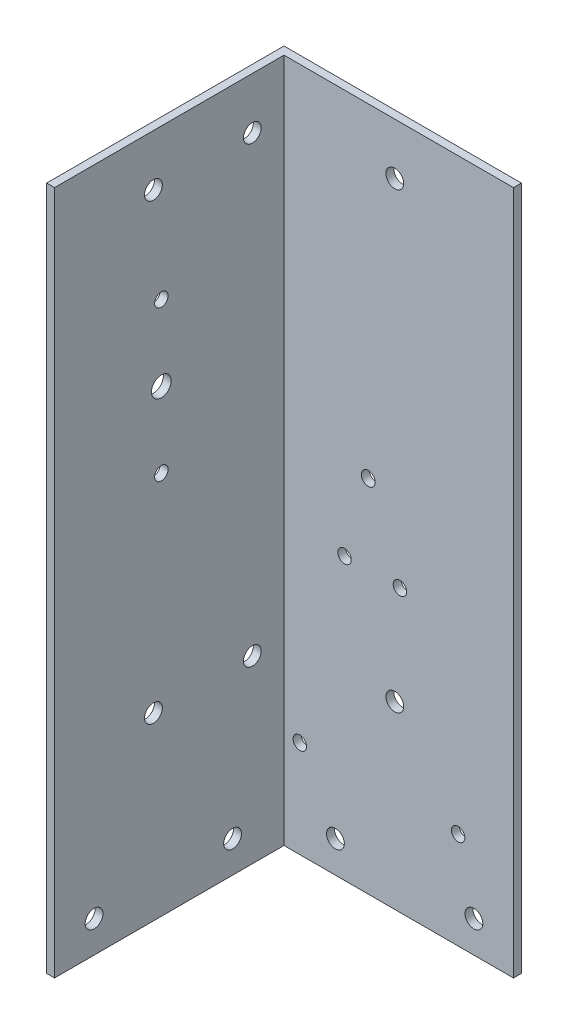
SolidWorks part; units mm, degrees
ref_plane "Ebene vorne" through (0, 0, 0) normal (0, 0, 1) x (1, 0, 0)
ref_plane "Ebene oben" through (0, 0, 0) normal (0, 1, 0) x (1, 0, 0)
ref_plane "Ebene rechts" through (0, 0, 0) normal (1, 0, 0) x (0, 0, -1)
sketch "Skizze1" plane through (0, 0, 0) normal (0, 1, 0) x (1, 0, 0)
  line L0 (0, 0) -> (0, -60)
  line L1 (0, 0) -> (60, 0)
  dimension "D1" = 60
  dimension "D2" = 60
extrude "Linear-Austragen-Dünn1" add sketch "Skizze1" along normal blind 173 thin thin type one direction wall 2
hole_wizard "Durchgangsloch für M41" positions "Skizze2" profile "Skizze3" hole size "M4" standard "DIN" end condition up to next
sketch "Skizze2" plane through (0, 0, 0) normal (-1, 0, 0) x (0, 0, 1)
  line L2 (10, 160) -> (35, 160) construction
  line L4 (60, 173) -> (0, 173) construction
  line L5 (0, 173) -> (0, 0) construction
  point P0 (35, 160)
  point P3 (10, 160)
  dimension "D1" = 13
  dimension "D2" = 25
  dimension "D3" = 10
sketch "Skizze3" plane through (0, 160, 35) normal (0, 1, 0) x (0, 0, 1)
  line L0 (0, 0) -> (0, 2)
  line L1 (0, 2) -> (2.25, 2)
  line L2 (2.25, 2) -> (2.25, 0)
  line L5 (2.25, 0) -> (0, 0)
  line L11 (0, -6.35) -> (0, 107.95) construction
  dimension "Bohrerdurchmesser" = 4.5
  dimension "Bohrungstiefe" = 2
hole_wizard "Durchgangsloch für M42" positions "Skizze4" profile "Skizze5" hole size "M4" standard "DIN" end condition up to next
sketch "Skizze4" plane through (0, 0, 0) normal (-1, 0, 0) x (0, 0, 1)
  line L0 (15, 8) -> (50, 8) construction
  line L2 (10, 45.5) -> (35, 45.5) construction
  line L4 (0, 173) -> (0, 0) construction
  circle A0 centre (35, 160) radius 2.25 construction
  point P0 (35, 45.5)
  point P8 (10, 45.5)
  point P12 (50, 8)
  point P15 (15, 8)
  dimension "D1" = 152
  dimension "D2" = 37.5
  dimension "D3" = 10
  dimension "D4" = 25
  dimension "D5" = 15
  dimension "D6" = 35
sketch "Skizze5" plane through (0, 45.5, 35) normal (0, 1, 0) x (0, 0, 1)
  line L0 (0, 0) -> (0, 2)
  line L1 (0, 2) -> (2.25, 2)
  line L2 (2.25, 2) -> (2.25, 0)
  line L5 (2.25, 0) -> (0, 0)
  line L11 (0, -6.35) -> (0, 107.95) construction
  dimension "Bohrerdurchmesser" = 4.5
  dimension "Bohrungstiefe" = 2
hole_wizard "Durchgangsloch für M43" positions "Skizze6" profile "Skizze7" hole size "M4" standard "DIN" end condition up to next
sketch "Skizze6" plane through (0, 0, 0) normal (0, 0, -1) x (-1, 0, 0)
  line L0 (0, 173) -> (-60, 173) construction
  line L1 (0, 173) -> (0, 0) construction
  line L2 (-30, 160) -> (-30, 45.5) construction
  line L4 (-50, 8) -> (-15, 8) construction
  point P0 (-30, 45.5)
  point P9 (-50, 8)
  point P12 (-15, 8)
  point P15 (-30, 160)
  dimension "D1" = 13
  dimension "D2" = 30
  dimension "D3" = 114.5
  dimension "D4" = 152
  dimension "D5" = 15
  dimension "D6" = 35
sketch "Skizze7" plane through (30, 45.5, 0) normal (1, 0, 0) x (0, 1, 0)
  line L0 (0, 0) -> (0, 2)
  line L1 (0, 2) -> (2.25, 2)
  line L2 (2.25, 2) -> (2.25, 0)
  line L5 (2.25, 0) -> (0, 0)
  line L11 (0, -6.35) -> (0, 107.95) construction
  dimension "Bohrerdurchmesser" = 4.5
  dimension "Bohrungstiefe" = 2
hole_wizard "Durchgangsloch für M31" positions "Skizze8" profile "Skizze9" hole size "M3" standard "DIN" end condition up to next
sketch "Skizze8" plane through (0, 0, 0) normal (-1, 0, 0) x (0, 0, 1)
  line L0 (33, 135) -> (33, 97) construction
  line L2 (60, 173) -> (60, 0) construction
  line L3 (60, 173) -> (0, 173) construction
  point P0 (33, 97)
  point P3 (33, 135)
  dimension "D1" = 27
  dimension "D2" = 38
  dimension "D3" = 38
sketch "Skizze9" plane through (0, 97, 33) normal (0, 1, 0) x (0, 0, 1)
  line L0 (0, 0) -> (0, 2)
  line L1 (0, 2) -> (1.7, 2)
  line L2 (1.7, 2) -> (1.7, 0)
  line L5 (1.7, 0) -> (0, 0)
  line L11 (0, -6.35) -> (0, 107.95) construction
  dimension "Bohrerdurchmesser" = 3.4
  dimension "Bohrungstiefe" = 2
hole_wizard "Ø5.0 (5) Durchmesser Bohrung1" positions "Skizze10" profile "Skizze11" hole size "Ø5.0" standard "DIN" end condition up to next
sketch "Skizze10" plane through (0, 0, 0) normal (-1, 0, 0) x (0, 0, 1)
  line L1 (0, 173) -> (0, 0) construction
  line L2 (60, 173) -> (0, 173) construction
  point P0 (33, 116)
  dimension "D1" = 33
  dimension "D2" = 57
sketch "Skizze11" plane through (0, 116, 33) normal (0, 1, 0) x (0, 0, 1)
  line L0 (0, 0) -> (0, 2)
  line L1 (0, 2) -> (2.5, 2)
  line L2 (2.5, 2) -> (2.5, 0)
  line L5 (2.5, 0) -> (0, 0)
  line L11 (0, -6.35) -> (0, 107.95) construction
  dimension "Bohrerdurchmesser" = 5
  dimension "Bohrungstiefe" = 2
hole_wizard "Durchgangsloch für M32" positions "Skizze12" profile "Skizze13" hole size "M3" standard "DIN" end condition up to next
sketch "Skizze12" plane through (0, 0, 0) normal (0, 0, -1) x (-1, 0, 0)
  line L0 (-31.3, 71) -> (-17.3, 71) construction
  line L2 (0, 173) -> (0, 0) construction
  line L3 (0, 173) -> (-60, 173) construction
  point P0 (-31.3, 71)
  point P3 (-17.3, 71)
  dimension "D1" = 17.3
  dimension "D2" = 14
  dimension "D3" = 102
sketch "Skizze13" plane through (31.3, 71, 0) normal (1, 0, 0) x (0, 1, 0)
  line L0 (0, 0) -> (0, 2)
  line L1 (0, 2) -> (1.7, 2)
  line L2 (1.7, 2) -> (1.7, 0)
  line L5 (1.7, 0) -> (0, 0)
  line L11 (0, -6.35) -> (0, 107.95) construction
  dimension "Bohrerdurchmesser" = 3.4
  dimension "Bohrungstiefe" = 2
hole_wizard "Durchgangsloch für M33" positions "Skizze14" profile "Skizze15" hole size "M3" standard "DIN" end condition up to next
sketch "Skizze14" plane through (0, 0, 0) normal (0, 0, -1) x (-1, 0, 0)
  line L0 (-46, 24.5) -> (-6, 24.5) construction
  line L2 (0, 173) -> (-60, 173) construction
  line L3 (0, 173) -> (0, 0) construction
  point P0 (-46, 24.5)
  point P3 (-6, 24.5)
  dimension "D1" = 148.5
  dimension "D2" = 6
  dimension "D3" = 40
sketch "Skizze15" plane through (46, 24.5, 0) normal (1, 0, 0) x (0, 1, 0)
  line L0 (0, 0) -> (0, 2)
  line L1 (0, 2) -> (1.7, 2)
  line L2 (1.7, 2) -> (1.7, 0)
  line L5 (1.7, 0) -> (0, 0)
  line L11 (0, -6.35) -> (0, 107.95) construction
  dimension "Bohrerdurchmesser" = 3.4
  dimension "Bohrungstiefe" = 2
hole_wizard "Ø3.5 (3.5) Durchmesser Bohrung1" positions "Skizze16" profile "Skizze17" hole size "Ø3.5" standard "DIN" end condition up to next
sketch "Skizze16" plane through (0, 0, 0) normal (0, 0, -1) x (-1, 0, 0)
  line L0 (0, 173) -> (0, 0) construction
  line L1 (0, 173) -> (-60, 173) construction
  point P0 (-23.3, 91)
  dimension "D1" = 23.3
  dimension "D2" = 82
sketch "Skizze17" plane through (23.3, 91, 0) normal (1, 0, 0) x (0, 1, 0)
  line L0 (0, 0) -> (0, 2)
  line L1 (0, 2) -> (1.75, 2)
  line L2 (1.75, 2) -> (1.75, 0)
  line L5 (1.75, 0) -> (0, 0)
  line L11 (0, -6.35) -> (0, 107.95) construction
  dimension "Bohrerdurchmesser" = 3.5
  dimension "Bohrungstiefe" = 2
